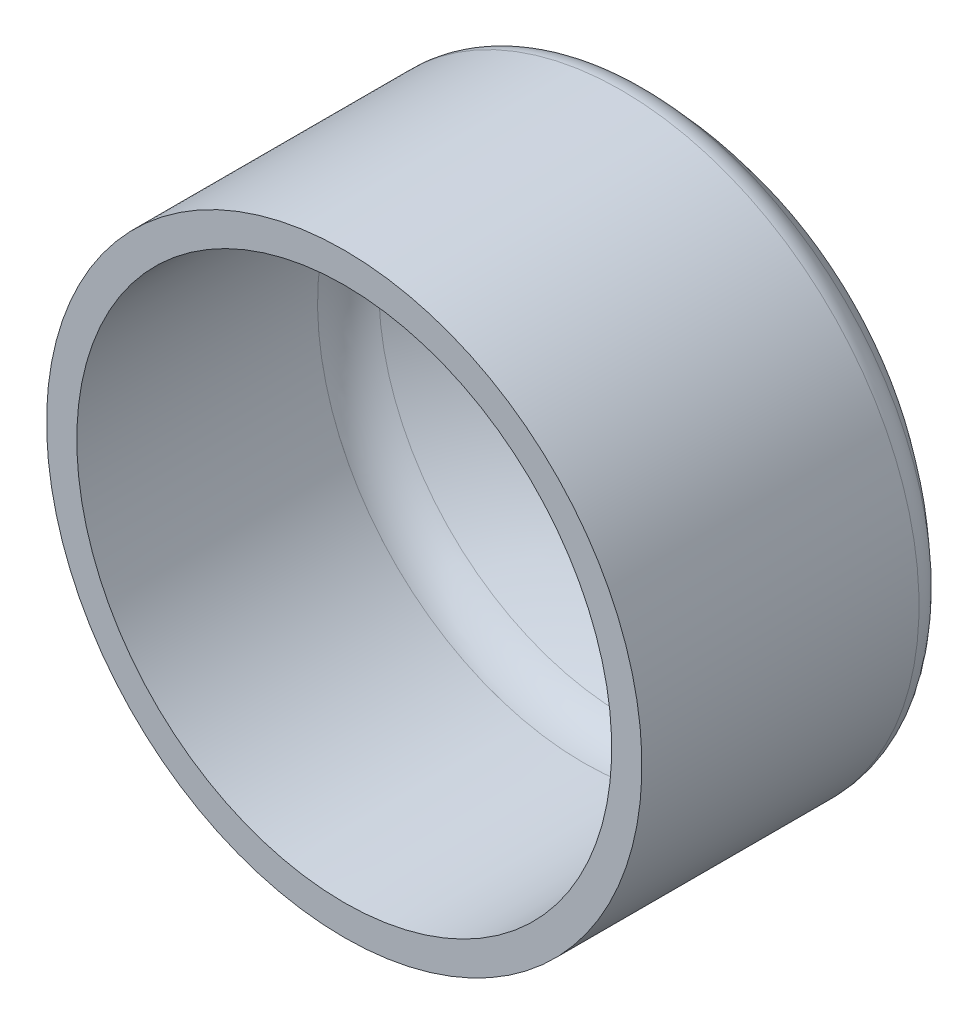
SolidWorks part; units mm, degrees
ref_plane "Front Plane" through (0, 0, 0) normal (0, 0, 1) x (1, 0, 0)
ref_plane "Top Plane" through (0, 0, 0) normal (0, 1, 0) x (1, 0, 0)
ref_plane "Right Plane" through (0, 0, 0) normal (1, 0, 0) x (0, 0, -1)
sketch "Sketch1" plane through (0, 0, 0) normal (1, 0, 0) x (0, 0, -1)
  line L0 (-44.3992, 0) -> (44.3992, 0) construction
  line L1 (-44.3992, -57.3786) -> (-44.3992, 57.3786) construction
  line L2 (-44.3992, -57.3786) -> (-44.3992, -63.8556) construction
  line L3 (6.9088, -57.0357) -> (6.9088, 57.0357) construction
  line L4 (6.9088, -57.0357) -> (6.9088, 57.0357) construction
  line L5 (-44.3992, -63.8556) -> (10.3632, -63.8556) construction
  line L6 (-44.3992, 57.3786) -> (-44.3992, 63.8556) construction
  line L7 (-44.3992, 63.8556) -> (10.3632, 63.8556) construction
  line L8 (6.9088, 57.0357) -> (6.9108, 57.0357) construction
  line L9 (6.9088, -57.0357) -> (6.9108, -57.0357) construction
  line L10 (10.3632, -63.8556) -> (17.7118, -63.8556) construction
  line L11 (10.3632, 63.8556) -> (17.7118, 63.8556) construction
  line L12 (-44.3992, -57.3786) -> (6.9088, -57.0357) construction
  line L13 (-44.3992, 57.3786) -> (6.9088, 57.0357) construction
  arc A0 (15.9267, -52.9092) -> (15.9267, 52.9092) centre (-45.339, 0) ccw construction
  arc A1 (6.9108, -57.0357) -> (15.9267, -52.9092) centre (6.9108, -45.1231) ccw construction
  arc A2 (15.9267, 52.9092) -> (6.9108, 57.0357) centre (6.9108, 45.1231) ccw construction
  arc A4 (17.7118, -63.8556) -> (17.7118, 63.8556) centre (-45.339, 0) ccw construction
  point P0 (35.6108, 0)
  point P4 (0, 0)
  point P9 (-44.3992, 0)
  point P13 (6.9088, 0)
  point P15 (6.9088, 0)
  dimension "Int. Dome Rad" = 80.9498
  dimension "Int. Dome Fillet" = 11.9126
  dimension "Dome Thickness" = 8.7884
  dimension "Socket to Dome" = 28.702
  dimension "Socket Depth" = 51.308
  dimension "Socket Bottom Dia" = 114.0714
  dimension "Socket Top Dia" = 114.7572
  dimension "Wall Thickness" = 6.477
  dimension "Ext. Body Length" = 54.7624
sketch "Sketch2" plane through (0, 0, 0) normal (1, 0, 0) x (0, 0, -1)
  line L6 (35.6108, 0) -> (44.3992, 0)
  line L7 (-44.3992, -57.3786) -> (-44.3992, -63.8556)
  line L8 (-44.3992, -63.8556) -> (17.7118, -63.8556)
  line L9 (-44.3992, -57.3786) -> (6.9088, -57.0357)
  line L10 (6.9088, -57.0357) -> (6.9108, -57.0357)
  arc A6 (17.7118, -63.8556) -> (17.7118, 63.8556) centre (-45.339, 0) ccw construction
  arc A7 (6.9108, -57.0357) -> (15.9267, -52.9092) centre (6.9108, -45.1231) ccw construction
  arc A8 (15.9267, -52.9092) -> (15.9267, 52.9092) centre (-45.339, 0) ccw construction
  arc A9 (17.7118, -63.8556) -> (44.3992, 0) centre (-45.339, 0) ccw
  arc A10 (6.9108, -57.0357) -> (15.9267, -52.9092) centre (6.9108, -45.1231) ccw
  arc A11 (15.9267, -52.9092) -> (35.6108, 0) centre (-45.339, 0) ccw
revolve "Revolve1" add sketch "Sketch2" angle 360 about L0
fillet "Fillet1" radius 6.35 1 edges at (0, -63.8556, -17.7118)
sketch "Sketch3" plane through (0, 0, 44.3992) normal (0, 0, 1) x (1, 0, 0)
  circle A2 centre (0, 0) radius 57.3786 construction
  circle A3 centre (0, 0) radius 57.3786
  point P3 (-57.3786, 0)
  point P4 (0, 57.3786)
  point P5 (57.3786, 0)
  point P6 (0, -57.3786)
